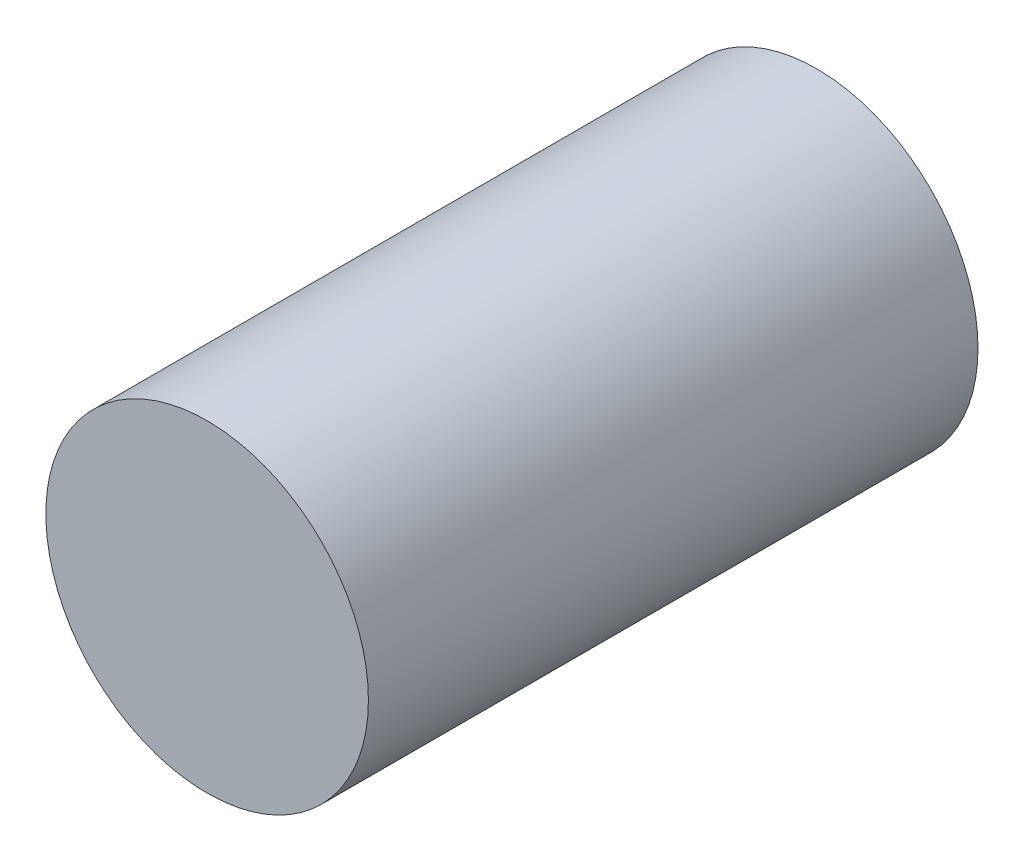
SolidWorks part; units mm, degrees
ref_plane "前视" through (0, 0, 0) normal (0, 0, 1) x (1, 0, 0)
ref_plane "上视" through (0, 0, 0) normal (0, 1, 0) x (1, 0, 0)
ref_plane "右视" through (0, 0, 0) normal (1, 0, 0) x (0, 0, -1)
sketch "草图1" plane through (0, 0, 0) normal (0, 0, 1) x (1, 0, 0)
  circle A0 centre (0, 0) radius 3.175
extrude "凸台-拉伸1" add sketch "草图1" along normal blind 12
